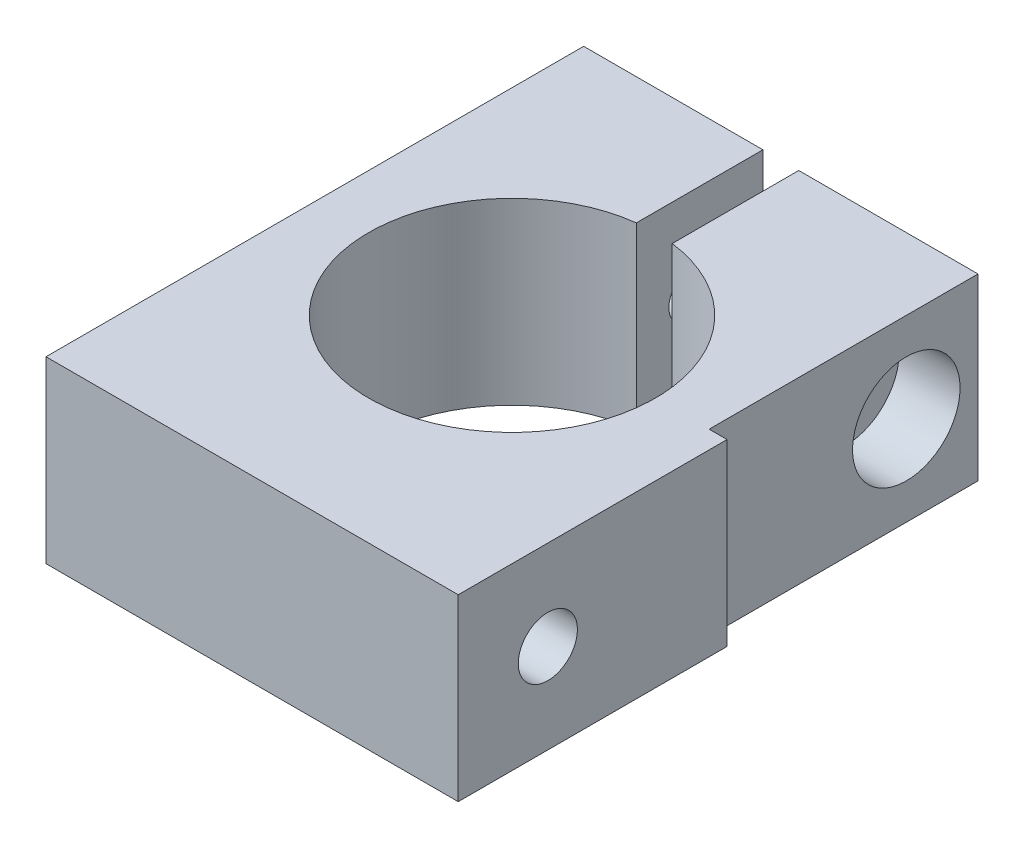
SolidWorks part; units mm, degrees
material "1060 合金"
ref_plane "前视基准面" through (0, 0, 0) normal (0, 0, 1) x (1, 0, 0)
ref_plane "上视基准面" through (0, 0, 0) normal (0, 1, 0) x (1, 0, 0)
ref_plane "右视基准面" through (0, 0, 0) normal (1, 0, 0) x (0, 0, -1)
sketch "草图1" plane through (0, 0, 0) normal (0, 1, 0) x (1, 0, 0)
  line L0 (0, 0) -> (0, 20.2002) construction
  line L1 (11, -15) -> (-11, -15)
  line L2 (11, -15) -> (11, 15)
  line L3 (11, 15) -> (1, 15)
  line L4 (-11, -15) -> (-11, 15)
  line L5 (11, -15) -> (-11, 15) construction
  line L6 (11, 15) -> (-11, -15) construction
  line L7 (0, 0) -> (0, -22.3102) construction
  line L8 (-1, 15) -> (-11, 15)
  line L10 (-1, 15) -> (-1, 7.9373)
  line L12 (1, 15) -> (1, 7.9373)
  line L13 (-1, 15) -> (1, 7.9373) construction
  line L14 (-1, 7.9373) -> (1, 15) construction
  arc A0 (-1, 7.9373) -> (1, 7.9373) centre (0, 0) ccw
  point P10 (0, 11.4686)
  dimension "D1" = 16
  dimension "D2" = 15
  dimension "D3" = 15
  dimension "D4" = 22
  dimension "D5" = 2
  dimension "D6" = 0
extrude "凸台-拉伸1" add sketch "草图1" along normal mid plane 10
hole_wizard "打孔尺寸(%根据)内六角圆柱头螺钉的类型1" positions "草图3" profile "草图4" counterbore size "M3" standard "GB"
sketch "草图3" plane through (11, 0, 0) normal (1, 0, 0) x (0, 0, -1)
  line L0 (15, 5) -> (15, -5) construction
  point P0 (11, 0)
  dimension "D1" = 4
sketch "草图4" plane through (11, 0, -11) normal (0, 1, 0) x (0, 0, -1)
  line L0 (0, 0) -> (0, 10)
  line L1 (0, 10) -> (1.6, 10)
  line L3 (1.6, 10) -> (1.6, 3.4)
  line L4 (1.6, 3.4) -> (3, 3.4)
  line L5 (3, 3.4) -> (3, 0)
  line L7 (3, 0) -> (0, 0)
  line L11 (0, -6.35) -> (0, 107.95) construction
  dimension "通孔孔直径" = 3.2
  dimension "通孔孔深度" = 10
  dimension "柱形沉头孔直径" = 6
  dimension "柱形沉头孔深度" = 3.4
hole_wizard "M3 螺纹孔1" positions "草图6" profile "草图5" tap size "M3" standard "GB" end condition up to next
sketch "草图6" plane through (-11, 0, 0) normal (-1, 0, 0) x (0, 0, 1)
  point P0 (-11, 0)
sketch "草图5" plane through (-11, 0, -11) normal (0, 1, 0) x (0, 0, 1)
  line L0 (0, 0) -> (0, 10)
  line L1 (0, 10) -> (1.25, 10)
  line L2 (1.25, 10) -> (1.25, 0)
  line L5 (1.25, 0) -> (0, 0)
  line L11 (0, -6.35) -> (0, 107.95) construction
  dimension "通孔螺纹孔钻头直径" = 2.5
  dimension "通孔螺纹孔钻头深度" = 10
cosmetic thread "孔螺蚊线1" parameters "D2"=3
sketch "草图9" plane through (11, 0, 0) normal (1, 0, 0) x (0, 0, -1)
  line L0 (-15, 5) -> (15, 5) construction
  line L1 (-15, -5) -> (0, -5)
  line L2 (-15, -5) -> (-15, 5)
  line L3 (-15, 5) -> (0, 5)
  line L4 (0, -5) -> (0, 5)
extrude "凸台-拉伸2" add sketch "草图9" along normal blind 1
hole_wizard "M4 螺纹孔1" positions "草图8" profile "草图7" tap size "M4" standard "GB"
sketch "草图8" plane through (12, 0, 7) normal (-1, 0, 0) x (0, 0, 1)
  point P11 (3, 0)
  dimension "D1" = 10
sketch "草图7" plane through (12, 0, 10) normal (0, 1, 0) x (0, 0, -1)
  line L0 (0, 0) -> (0, 10.4914)
  line L1 (0, 10.4914) -> (1.65, 9.5)
  line L2 (1.65, 9.5) -> (1.65, 0)
  line L5 (1.65, 0) -> (0, 0)
  line L10 (0, 10.4914) -> (-1.65, 9.5) construction
  line L11 (0, -6.35) -> (0, 107.95) construction
  dimension "螺纹孔钻头直径" = 3.3
  dimension "螺纹孔钻头深度" = 9.5
  dimension "导头角度" = 118
cosmetic thread "孔螺蚊线2" parameters "D1"=6, "D2"=4
